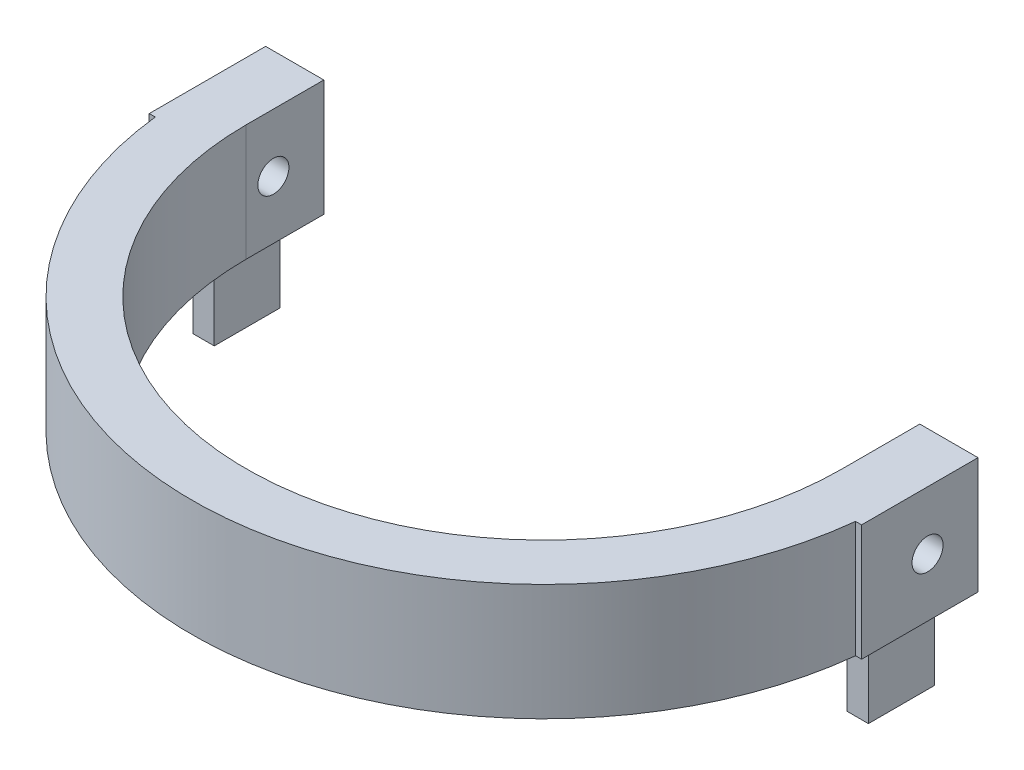
SolidWorks part; units mm, degrees
material "1060 Alloy"
ref_plane "Front Plane" through (0, 0, 0) normal (0, 0, 1) x (1, 0, 0)
ref_plane "Top Plane" through (0, 0, 0) normal (0, 1, 0) x (1, 0, 0)
ref_plane "Right Plane" through (0, 0, 0) normal (1, 0, 0) x (0, 0, -1)
sketch "Sketch1" plane through (0, 0, 0) normal (0, 1, 0) x (1, 0, 0)
  line L0 (-1000, 0) -> (-104.805, 0) construction
  line L1 (0, -1000) -> (0, 49000) construction
  line L2 (91.805, -10) -> (90.2527, -10)
  line L3 (-76.805, 0) -> (76.805, 0)
  line L7 (-91.805, -10) -> (-90.2527, -10)
  line L9 (104.805, 0) -> (49000, 0) construction
  line L10 (-76.805, 0) -> (-76.805, 20)
  line L12 (-76.805, 0) -> (76.805, 0) construction
  line L13 (91.805, 20) -> (91.805, -10)
  line L14 (76.805, 20) -> (91.805, 20)
  line L17 (-76.805, 20) -> (-91.805, 20)
  line L18 (76.805, 0) -> (76.805, 20)
  line L19 (-91.805, 20) -> (-91.805, -10)
  arc A0 (-90.2527, -10) -> (90.2527, -10) centre (0, 0) ccw
  arc A1 (-76.805, 0) -> (76.805, 0) centre (0, 0) ccw
  dimension "D1" = 181.61
  dimension "D2" = 14
  dimension "D3" = 30
  dimension "D4" = 15
extrude "Boss-Extrude1" add sketch "Sketch1" against normal blind 60
sketch "Sketch25" plane through (0, -60, 0) normal (0, -1, 0) x (-1, 0, 0)
  line L0 (76.805, 20) -> (91.805, -10)
  line L1 (91.805, -10) -> (76.805, -10)
  line L2 (76.805, -10) -> (91.805, 20)
  line L3 (-91.805, -10) -> (-76.805, 20)
  line L4 (81.555, -3.5) -> (87.055, -3.5)
  line L5 (81.555, -3.5) -> (81.555, 13.5)
  line L6 (81.555, 13.5) -> (87.055, 13.5)
  line L7 (87.055, -3.5) -> (87.055, 13.5)
  line L8 (81.555, -3.5) -> (87.055, 13.5) construction
  line L9 (81.555, 13.5) -> (87.055, -3.5) construction
  line L10 (-76.805, 20) -> (-77.8097, -10)
  line L11 (-77.8097, -10) -> (-91.805, -10)
  line L12 (-77.8097, -10) -> (-91.805, 20)
  line L14 (-87.055, -3.5) -> (-81.555, -3.5)
  line L15 (-87.055, -3.5) -> (-87.055, 13.5)
  line L16 (-87.055, 13.5) -> (-81.555, 13.5)
  line L17 (-81.555, -3.5) -> (-81.555, 13.5)
  line L18 (-87.055, -3.5) -> (-81.555, 13.5) construction
  line L19 (-87.055, 13.5) -> (-81.555, -3.5) construction
  point P4 (84.305, 5)
  point P16 (-84.305, 5)
  dimension "D1" = 5.5
  dimension "D2" = 17
  dimension "D3" = 17
  dimension "D4" = 5.5
extrude "Boss-Extrude3" add sketch "Sketch25" along normal blind 20 contours L15 L16 L17 L14 | L5 L6 L7 L4
ref_plane "Plane4" through (0, 0, 90) normal (0, 0, 1) x (1, 0, 0)
fillet "Fillet1" radius 2.3 8 edges at (84.305, -60, 3.5) (81.555, -60, -5) (84.305, -60, -13.5) (87.055, -60, -5) (-87.055, -60, -5) (-84.305, -60, -13.5) (-84.305, -60, 3.5) (-81.555, -60, -5)
sketch "Sketch30" plane through (0, 0, -20) normal (0, 0, -1) x (-1, 0, 0)
  line L0 (-91.805, -60) -> (-91.805, 0) construction
  line L1 (91.805, 0) -> (-91.805, 0)
  line L2 (91.805, 0) -> (91.805, -30)
  line L3 (91.805, -30) -> (-91.805, -30)
  line L4 (-91.805, 0) -> (-91.805, -30)
  dimension "D1" = 30
extrude "Cut-Extrude19" cut sketch "Sketch30" against normal through all both and the other way through all
sketch "Sketch31" plane through (91.805, 0, 0) normal (1, 0, 0) x (0, 0, -1)
  line L0 (-10, -60) -> (-10, -30) construction
  line L1 (-10, -30) -> (20, -30) construction
  circle A0 centre (7, -45) radius 4
  dimension "D1" = 17
  dimension "D2" = 15
  dimension "D3" = 8
extrude "Cut-Extrude20" cut sketch "Sketch31" against normal through all
